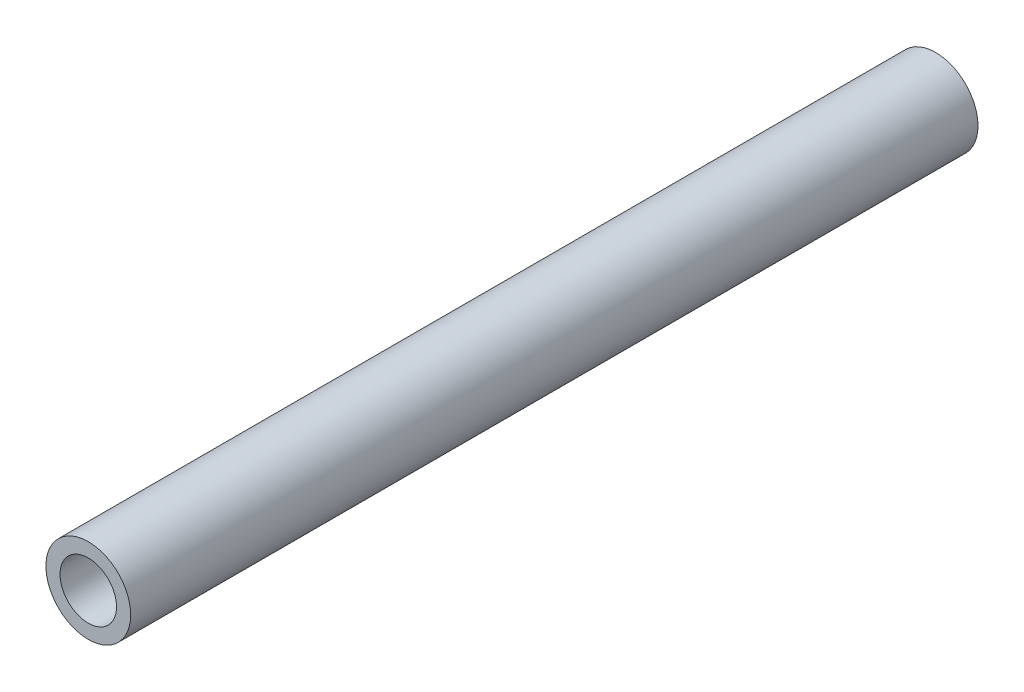
SolidWorks part; units mm, degrees
material "Thornel VCB-20 Carbon Cloth"
ref_plane "Front Plane" through (0, 0, 0) normal (0, 0, 1) x (1, 0, 0)
ref_plane "Top Plane" through (0, 0, 0) normal (0, 1, 0) x (1, 0, 0)
ref_plane "Right Plane" through (0, 0, 0) normal (1, 0, 0) x (0, 0, -1)
sketch "Sketch1" plane through (0, 0, 0) normal (0, 0, 1) x (1, 0, 0)
  circle A0 centre (-0.9922, 0.0115) radius 1.5
  circle A1 centre (-0.9922, 0.0115) radius 1
  dimension "D1" = 3
  dimension "D2" = 2
extrude "Boss-Extrude1" add sketch "Sketch1" along normal blind 30
